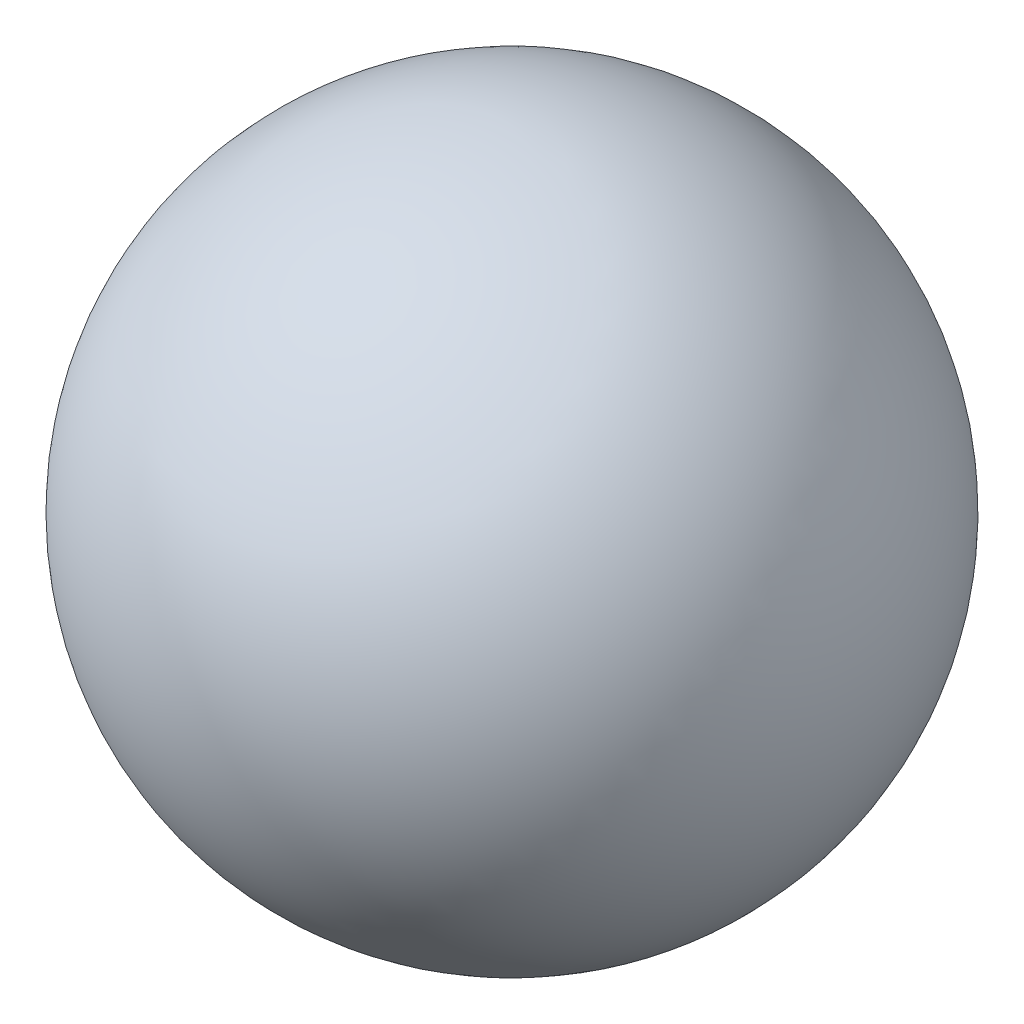
SolidWorks part; units mm, degrees
ref_plane "Front Plane" through (0, 0, 0) normal (0, 0, 1) x (1, 0, 0)
ref_plane "Top Plane" through (0, 0, 0) normal (0, 1, 0) x (1, 0, 0)
ref_plane "Right Plane" through (0, 0, 0) normal (1, 0, 0) x (0, 0, -1)
ref_plane "Plane1" through (-0.8869, -3.2034, 11.0451) normal (-0.0769, -0.2777, 0.9576) x (0.9944, 0.048, 0.0938)
sketch "Sketch2" plane through (-0.8869, -3.2034, 11.0451) normal (-0.0769, -0.2777, 0.9576) x (0.9944, 0.048, 0.0938)
  line L0 (0, -4.8749) -> (0, 4.8749)
  line L1 (0, 0) -> (4.8749, 0) construction
  arc A1 (0, -4.8749) -> (0, 4.8749) centre (0, 0) ccw
  dimension "D1" = 9.7499
  dimension "D2" = 4.8749
revolve "Revolve1" add sketch "Sketch2" angle 360 about L0
sketch "Sketch3" plane through (0, 0, 0) normal (1, 0, 0) x (0, 0, -1)
  line L0 (-0.5, 0) -> (-2.5, 0) construction
  line L2 (-2.5, -5.5) -> (-5.1651, -5.5)
  line L3 (-2.5, -5.5) -> (-2.5, 5.5)
  line L4 (-2.5, 5.5) -> (-5.1651, 5.5)
  line L5 (-5.1651, -5.5) -> (-5.1651, 5.5)
  dimension "D1" = 2
  dimension "D2" = 2.6651
  dimension "D3" = 11
